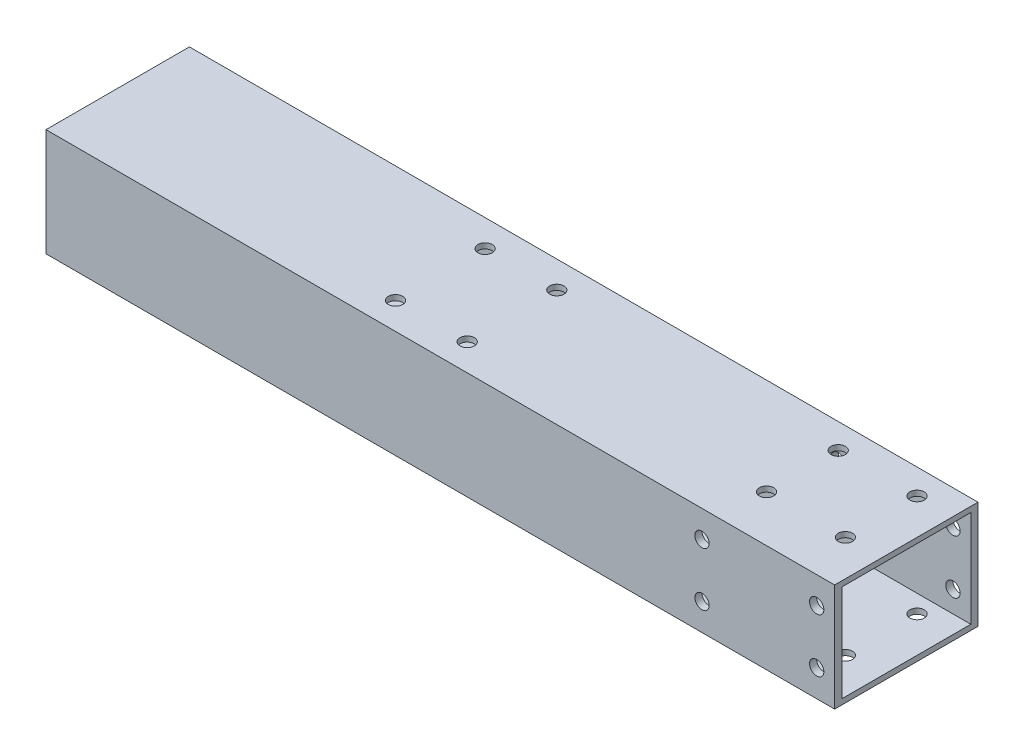
SolidWorks part; units mm, degrees
ref_plane "前视基准面" through (0, 0, 0) normal (0, 0, 1) x (1, 0, 0)
ref_plane "上视基准面" through (0, 0, 0) normal (0, 1, 0) x (1, 0, 0)
ref_plane "右视基准面" through (0, 0, 0) normal (1, 0, 0) x (0, 0, -1)
sketch "草图1" plane through (0, 0, 0) normal (1, 0, 0) x (0, 0, -1)
  line L1 (20, -15) -> (-20, -15)
  line L2 (20, -15) -> (20, 15)
  line L3 (20, 15) -> (-20, 15)
  line L4 (-20, -15) -> (-20, 15)
  line L5 (20, -15) -> (-20, 15) construction
  line L6 (20, 15) -> (-20, -15) construction
  line L7 (18, -13.5) -> (-18, -13.5)
  line L8 (18, -13.5) -> (18, 13.5)
  line L9 (18, 13.5) -> (-18, 13.5)
  line L10 (-18, -13.5) -> (-18, 13.5)
  line L11 (18, -13.5) -> (-18, 13.5) construction
  line L12 (18, 13.5) -> (-18, -13.5) construction
  point P0 (0, 0)
  point P6 (0, 0)
  dimension "D1" = 40
  dimension "D2" = 30
  dimension "D3" = 36
extrude "凸台-拉伸1" add sketch "草图1" along normal blind 220
sketch "草图2" plane through (0, 15, 0) normal (0, 1, 0) x (1, 0, 0)
  line L0 (220, 20) -> (220, -20) construction
  line L1 (220, -20) -> (0, -20) construction
  circle A0 centre (210, -7) radius 2
  circle A1 centre (210, 13) radius 2
  circle A2 centre (188, 13) radius 2
  circle A3 centre (188, -7) radius 2
  dimension "D1" = 22
  dimension "D2" = 22
  dimension "D3" = 20
  dimension "D4" = 20
  dimension "D5" = 10
  dimension "D6" = 10
  dimension "D7" = 4
  dimension "D8" = 4
  dimension "D9" = 4
  dimension "D10" = 4
  dimension "D11" = 13
  dimension "D12" = 13
extrude "切除-拉伸1" cut sketch "草图2" against normal through all
sketch "草图3" plane through (0, 15, 0) normal (0, 1, 0) x (1, 0, 0)
  line L0 (220, 20) -> (0, 20) construction
  line L1 (220, 20) -> (220, -20) construction
  circle A0 centre (90, 12.5) radius 2
  circle A1 centre (110, 12.5) radius 2
  circle A2 centre (110, -12.5) radius 2
  circle A3 centre (90, -12.5) radius 2
  dimension "D1" = 20
  dimension "D2" = 20
  dimension "D3" = 25
  dimension "D4" = 25
  dimension "D5" = 7.5
  dimension "D6" = 7.5
  dimension "D7" = 4
  dimension "D8" = 4
  dimension "D9" = 4
  dimension "D10" = 4
  dimension "D11" = 110
  dimension "D12" = 110
extrude "切除-拉伸2" cut sketch "草图3" against normal through all
sketch "草图4" plane through (0, 0, 20) normal (0, 0, 1) x (1, 0, 0)
  line L0 (220, 15) -> (220, -15) construction
  line L1 (220, 15) -> (0, 15) construction
  circle A0 centre (183, 7.5) radius 2
  circle A1 centre (215, 7.5) radius 2
  circle A2 centre (215, -7.5) radius 2
  circle A3 centre (183, -7.5) radius 2
  dimension "D1" = 15
  dimension "D2" = 15
  dimension "D3" = 5
  dimension "D4" = 5
  dimension "D5" = 37
  dimension "D6" = 37
  dimension "D7" = 4
  dimension "D8" = 4
  dimension "D9" = 4
  dimension "D10" = 4
  dimension "D11" = 7.5
  dimension "D12" = 7.5
extrude "切除-拉伸3" cut sketch "草图4" against normal through all
